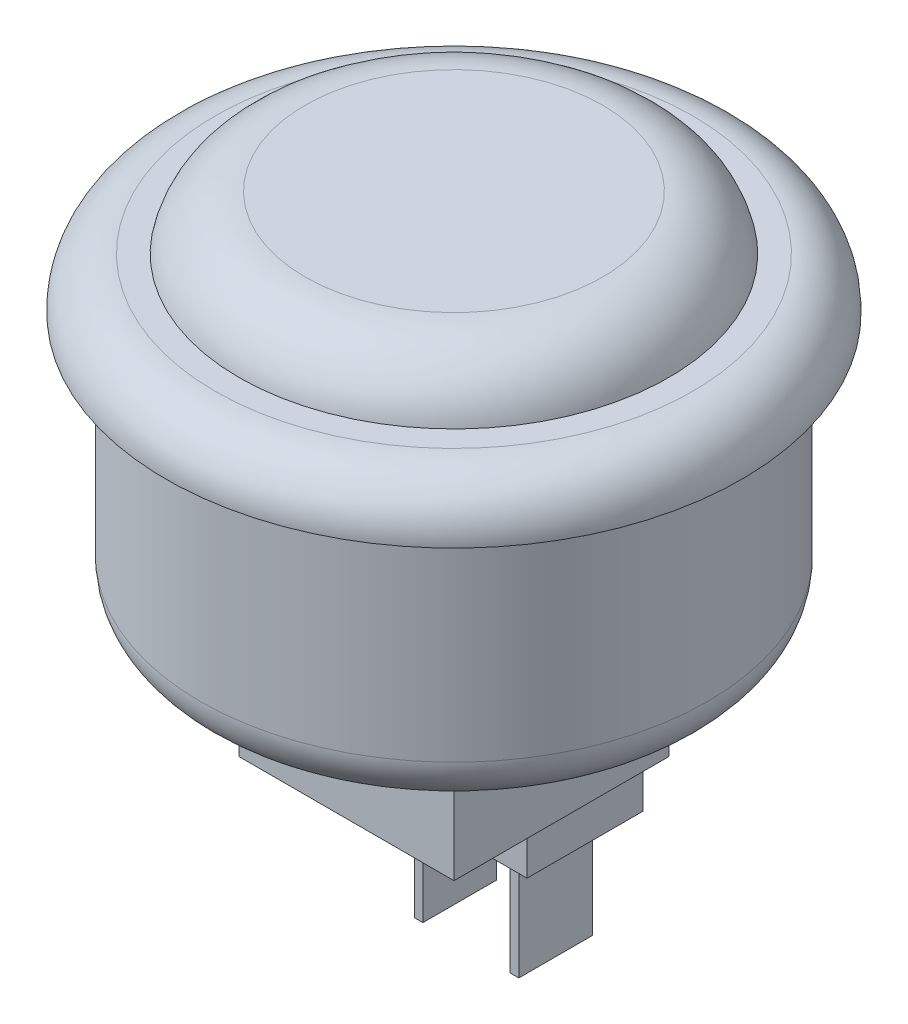
SolidWorks part; units mm, degrees
ref_plane "Alzado" through (0, 0, 0) normal (0, 0, 1) x (1, 0, 0)
ref_plane "Planta" through (0, 0, 0) normal (0, 1, 0) x (1, 0, 0)
ref_plane "Vista lateral" through (0, 0, 0) normal (1, 0, 0) x (0, 0, -1)
sketch "Croquis2" plane through (0, 0, 0) normal (0, 0, 1) x (1, 0, 0)
  line L0 (0, 0) -> (0, 44.3705) construction
  line L1 (0, 3.6794) -> (-8.6594, 3.6794)
  line L2 (-12.5, 0.5315) -> (-13.8881, 0.5315)
  line L3 (-16.75, -2.4685) -> (-14.75, -2.4685)
  line L4 (-14.75, -2.4685) -> (-14.75, -14.6702)
  line L5 (-11.9517, -17.4685) -> (0, -17.4685)
  line L6 (0, 3.6794) -> (0, -17.4685)
  arc A0 (-8.6594, 3.6794) -> (-12.5, 0.5315) centre (-8.6594, -0.2374) ccw
  arc A1 (-16.75, -2.4685) -> (-13.8881, 0.5315) centre (-13.8881, -2.3335) cw
  arc A2 (-14.75, -14.6702) -> (-11.9517, -17.4685) centre (-11.9517, -14.6702) ccw
  point P9 (0, 0)
  dimension "D5" = 3
  dimension "D6" = 2.8651
  dimension "D8" = 2.7983
  dimension "D9" = 3.9169
  dimension "D1" = 12.5
  dimension "D2" = 16.75
  dimension "D3" = 14.75
  dimension "D4" = 15
  dimension "D7" = 21.1479
revolve "Revolución1" add sketch "Croquis2" angle 360 about L0
sketch "Croquis3" plane through (0, -17.4685, 0) normal (0, -1, 0) x (1, 0, 0)
  line L1 (6.25, -6.25) -> (-6.25, -6.25)
  line L2 (6.25, -6.25) -> (6.25, 6.25)
  line L3 (6.25, 6.25) -> (-6.25, 6.25)
  line L4 (-6.25, -6.25) -> (-6.25, 6.25)
  line L5 (6.25, -6.25) -> (-6.25, 6.25) construction
  line L6 (6.25, 6.25) -> (-6.25, -6.25) construction
  point P0 (0, 0)
  dimension "D1" = 12.5
extrude "Saliente-Extruir1" add sketch "Croquis3" along normal blind 7.35
sketch "Croquis4" plane through (0, -24.8185, 0) normal (0, -1, 0) x (-1, 0, 0)
  line L0 (0, 0) -> (0, 6.25) construction
  line L1 (6.25, 6.25) -> (-6.25, 6.25) construction
  line L2 (-6.25, 3.125) -> (6.25, 3.125) construction
  line L3 (6.25, -6.25) -> (6.25, 6.25) construction
  line L4 (-6.25, 6.25) -> (-6.25, -6.25) construction
  line L5 (5.25, -1) -> (-5.25, 5.75) construction
  line L6 (5.25, 5.75) -> (-5.25, 5.75)
  line L7 (5.25, 5.75) -> (5.25, -1)
  line L8 (5.25, -1) -> (-5.25, -1)
  line L9 (-5.25, 5.75) -> (-5.25, -1)
  line L10 (-5.25, -1) -> (5.25, 5.75) construction
  line L11 (6.25, -6.25) -> (6.25, 6.25) construction
  point P11 (0, 3.125)
  point P12 (0, 3.125)
  dimension "D1" = 0.5
  dimension "D2" = 1
  dimension "D3" = 1
  dimension "D4" = 1
extrude "Saliente-Extruir2" add sketch "Croquis4" along normal blind 3
sketch "Croquis5" plane through (0, -27.8185, 0) normal (0, -1, 0) x (1, 0, 0)
  line L0 (0, 1) -> (0, -5.75) construction
  line L1 (5.25, 1) -> (-5.25, 1) construction
  line L2 (-5.25, -5.75) -> (5.25, -5.75) construction
  line L3 (-5.25, -2.875) -> (5.25, -2.875) construction
  line L4 (-5.25, 1) -> (-5.25, -5.75) construction
  line L5 (5.25, -5.75) -> (5.25, 1) construction
  line L7 (-2.54, -5.0171) -> (-3.04, -5.0171)
  line L8 (-2.54, -5.0171) -> (-2.54, -0.7329)
  line L9 (-2.54, -0.7329) -> (-3.04, -0.7329)
  line L10 (-3.04, -5.0171) -> (-3.04, -0.7329)
  line L11 (-2.54, -5.0171) -> (-3.04, -0.7329) construction
  line L12 (-2.54, -0.7329) -> (-3.04, -5.0171) construction
  point P13 (-2.79, -2.875)
  dimension "D1" = 2.875
  dimension "D2" = 2.54
  dimension "D3" = 2.1421
  dimension "D4" = 0.5
extrude "Saliente-Extruir3" add sketch "Croquis5" along normal blind 7
mirror "Simetría1" about plane through (0, 0, 0) normal (1, 0, 0) of "Saliente-Extruir3"
